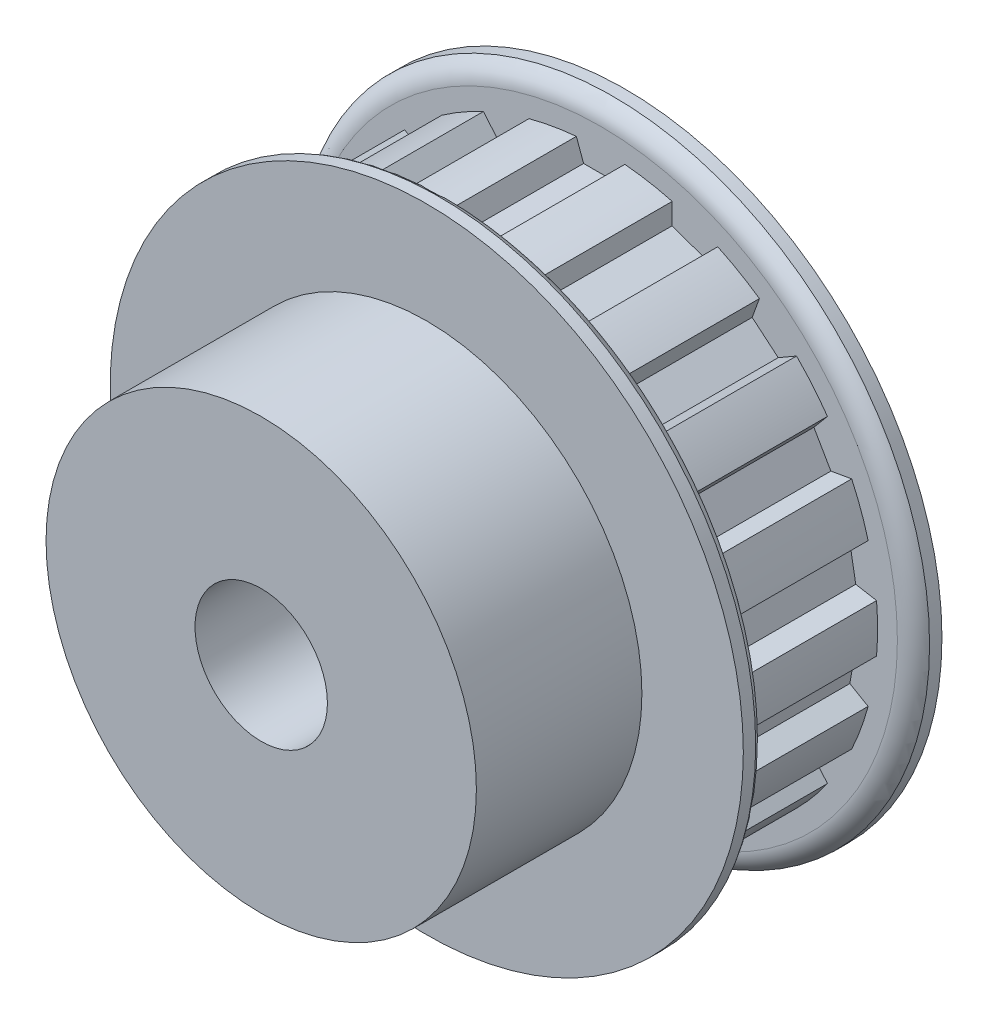
SolidWorks part; units mm, degrees
ref_plane "Front Plane" through (0, 0, 0) normal (0, 0, 1) x (1, 0, 0)
ref_plane "Top Plane" through (0, 0, 0) normal (0, 1, 0) x (1, 0, 0)
ref_plane "Right Plane" through (0, 0, 0) normal (1, 0, 0) x (0, 0, -1)
sketch "Sketch1" plane through (0, 0, 0) normal (0, 0, 1) x (1, 0, 0)
  line L0 (-2.3241, 26.4668) -> (-1.6307, 24.5618)
  line L1 (-1.6307, 24.5618) -> (1.6307, 24.5618)
  line L2 (1.6307, 24.5618) -> (2.3241, 26.4668)
  line L3 (-2.3241, 26.4668) -> (2.3241, 26.4668)
  line L4 (0, 0) -> (0, 24.5618) construction
  line L5 (0, 24.5618) -> (0, 28.1178) construction
  circle A0 centre (0, 0) radius 27.2923 construction
  circle A1 centre (0, 0) radius 30.3657 construction
  circle A2 centre (0, 0) radius 26.5686 construction
  point P6 (0, 26.4668)
  point P11 (0, 27.2923)
  point P13 (0, 30.3657)
  point P14 (0, 26.5686)
  dimension "D1" = 1.651
  dimension "PD" = 54.5846
  dimension "D2" = 0.8255
  dimension "OD" = 60.7314
  dimension "b" = 40
  dimension "bt" = 4.6482
  dimension "ht" = 1.905
  dimension "hs" = 3.556
sketch "Sketch2" plane through (0, 0, 0) normal (1, 0, 0) x (0, 0, -1)
  line L0 (-17.4625, 6.35) -> (17.4625, 6.35)
  line L1 (-17.4625, 6.35) -> (-17.4625, 20.6375)
  line L2 (-17.4625, 20.6375) -> (-1.5875, 20.6375)
  line L3 (-1.5875, 20.6375) -> (-1.5875, 30.3657)
  line L4 (-1.5875, 30.3657) -> (0.7874, 30.3657) construction
  line L5 (0.7874, 30.3657) -> (0.7874, 26.5686) construction
  line L6 (0.7874, 26.5686) -> (15.0876, 26.5686)
  line L7 (15.0876, 26.5686) -> (15.0876, 30.3657) construction
  line L8 (15.0876, 30.3657) -> (17.4625, 30.3657) construction
  line L9 (17.4625, 30.3657) -> (17.4625, 6.35)
  line L10 (-17.4625, 0) -> (17.4625, 0) construction
  line L13 (-1.5875, 30.3657) -> (-0.4001, 30.3657)
  line L14 (0.7874, 28.4672) -> (0.7874, 26.5686)
  line L15 (15.0876, 26.5686) -> (15.0876, 28.4672)
  line L16 (16.2751, 30.3657) -> (17.4625, 30.3657)
  arc A0 (0.7874, 28.4672) -> (-0.4001, 30.3657) centre (-1.324, 28.4672) ccw
  arc A1 (15.0876, 28.4672) -> (16.2751, 30.3657) centre (17.199, 28.4672) cw
  point P12 (0.7874, 28.4672)
  point P14 (-0.4001, 30.3657)
  point P20 (15.0876, 28.4672)
  point P21 (16.2751, 30.3657)
  point P25 (15.0876, 0)
  point P26 (0.7874, 0)
  dimension "OA" = 34.925
  dimension "Bore" = 12.7
  dimension "Hub Dia" = 41.275
  dimension "Outside Width" = 19.05
  dimension "Inside Width" = 14.3002
revolve "Revolve1" add sketch "Sketch2" angle 360 mid plane about L10
sketch "Sketch3" plane through (0, 0, 0) normal (0, 0, 1) x (1, 0, 0)
  line L0 (-1.6307, 24.5618) -> (1.6307, 24.5618) construction
  line L1 (1.6307, 24.5618) -> (2.3241, 26.4668) construction
  line L2 (-2.3241, 26.4668) -> (-1.6307, 24.5618) construction
  line L3 (-1.6307, 24.5618) -> (1.6307, 24.5618)
  line L4 (1.6307, 24.5618) -> (2.3241, 26.4668)
  line L5 (-2.3241, 26.4668) -> (-1.6307, 24.5618)
  circle A0 centre (0, 0) radius 26.5686 construction
  arc A1 (2.3241, 26.4668) -> (-2.3241, 26.4668) centre (0, 0) ccw
extrude "Cut-Extrude1" cut sketch "Sketch3" against normal up to vertex (15.0876 mm away) from vertex at -0.7874 starting at point (0, 26.5686, -0.7874)
pattern_circular "CirPattern1" count 18 over 360 about axis through (0, 0, 0) along (0, 0, 1) of "Cut-Extrude1"
equation "\"D2@Sketch1\" = \"D1@Sketch1\"/2"
